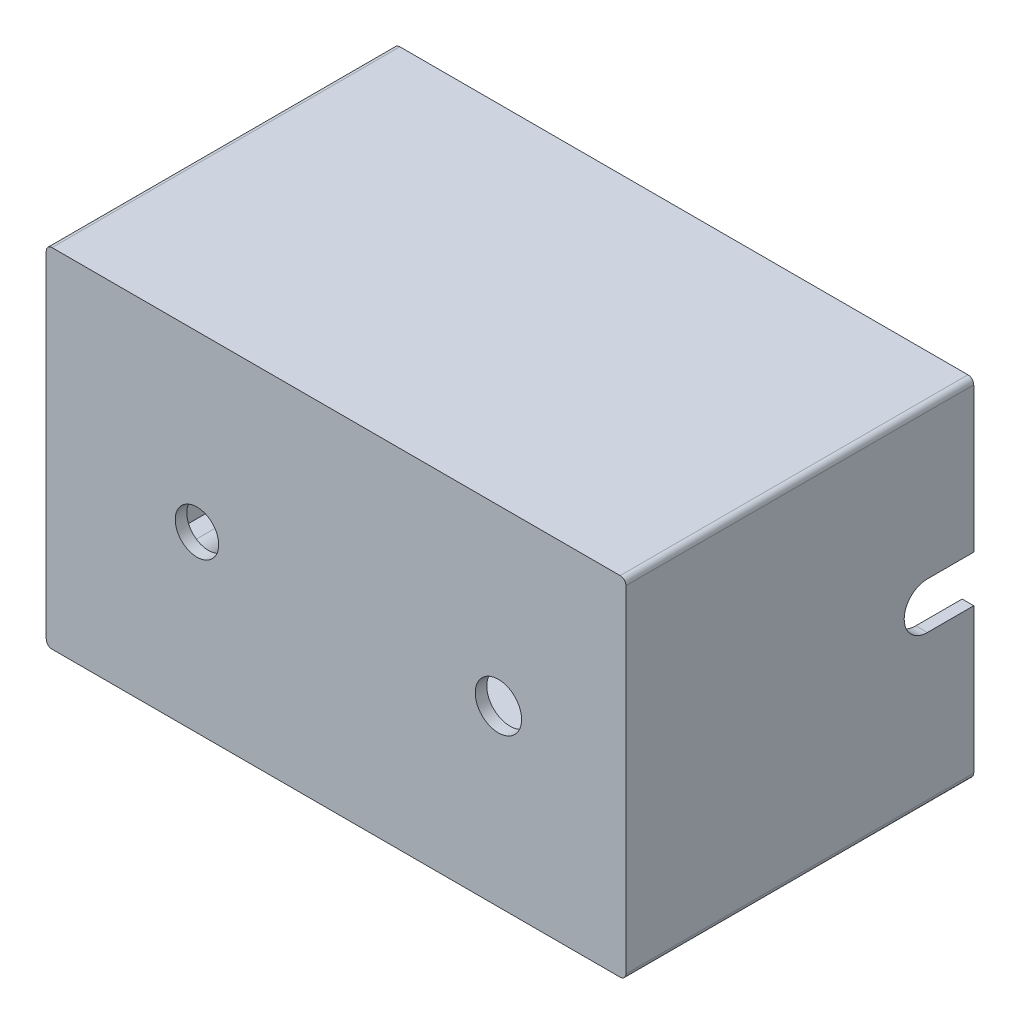
SolidWorks part; units mm, degrees
ref_plane "Piano frontale" through (0, 0, 0) normal (0, 0, 1) x (1, 0, 0)
ref_plane "Piano superiore" through (0, 0, 0) normal (0, 1, 0) x (1, 0, 0)
ref_plane "Piano destro" through (0, 0, 0) normal (1, 0, 0) x (0, 0, -1)
sketch "Sketch1" plane through (0, 0, 0) normal (0, 0, 1) x (1, 0, 0)
  line L1 (50, -30) -> (-50, -30)
  line L2 (50, -30) -> (50, 30)
  line L3 (50, 30) -> (-50, 30)
  line L4 (-50, -30) -> (-50, 30)
  line L5 (50, -30) -> (-50, 30) construction
  line L6 (50, 30) -> (-50, -30) construction
  point P0 (0, 0)
  dimension "D1" = 60
  dimension "D2" = 100
extrude "Boss-Extrude1" add sketch "Sketch1" along normal blind 60
shell "Shell1" thickness 2
sketch "Sketch2" plane through (0, 0, 60) normal (0, 0, 1) x (1, 0, 0)
  line L0 (-50, 0) -> (50, 0) construction
  line L1 (-50, 30) -> (-50, -30) construction
  line L2 (50, -30) -> (50, 30) construction
  circle A0 centre (-24, 0) radius 3.75
  circle A1 centre (28, 0) radius 4
  dimension "D1" = 7.5
  dimension "D2" = 8
  dimension "D3" = 24
  dimension "D4" = 28
extrude "Cut-Extrude1" cut sketch "Sketch2" against normal blind 60
sketch "Sketch3" plane through (0, 0, 58) normal (0, 0, -1) x (-1, 0, 0)
  line L0 (-42, 25) -> (-42, 28)
  line L1 (45, -25) -> (-45, -25) construction
  line L2 (45, -25) -> (45, 25) construction
  line L3 (45, 25) -> (-45, 25) construction
  line L4 (-45, -25) -> (-45, 25) construction
  line L5 (45, -25) -> (-45, 25) construction
  line L6 (45, 25) -> (-45, -25) construction
  line L7 (-48, 28) -> (48, 28) construction
  line L8 (-42, 28) -> (-48, 28)
  line L9 (-48, 28) -> (-48, 22)
  line L10 (-48, -28) -> (-48, 28) construction
  line L11 (-48, 22) -> (-45, 22)
  arc A0 (-45, 22) -> (-42, 25) centre (-45, 25) ccw
  circle A4 centre (-45, 25) radius 1.35
  point P0 (0, 0)
  dimension "D3" = 6
  dimension "D4" = 2.7
  dimension "D1" = 50
  dimension "D2" = 90
extrude "Boss-Extrude4" add sketch "Sketch3" along normal blind 58
mirror "Mirror1" about plane through (0, 0, 0) normal (1, 0, 0) of "Boss-Extrude4"
mirror "Mirror2" about plane through (0, 0, 0) normal (0, 1, 0) of "Mirror1", "Boss-Extrude4"
fillet "Fillet1" radius 1 4 edges at (-50, -30, 30) (50, -30, 30) (-50, 30, 30) (50, 30, 30)
sketch "Sketch4" plane through (50, 0, 0) normal (1, 0, 0) x (0, 0, -1)
  line L0 (0, -29) -> (0, 29) construction
  line L1 (-8, -4) -> (0, -4)
  line L2 (-8, -4) -> (-8, 4) construction
  line L3 (-8, 4) -> (0, 4)
  line L4 (0, -4) -> (0, 4)
  line L5 (0, 0) -> (-8, 0) construction
  arc A0 (-8, 4) -> (-8, -4) centre (-8, 0) ccw
  dimension "D1" = 8
  dimension "D2" = 8
extrude "Cut-Extrude2" cut sketch "Sketch4" against normal through all
